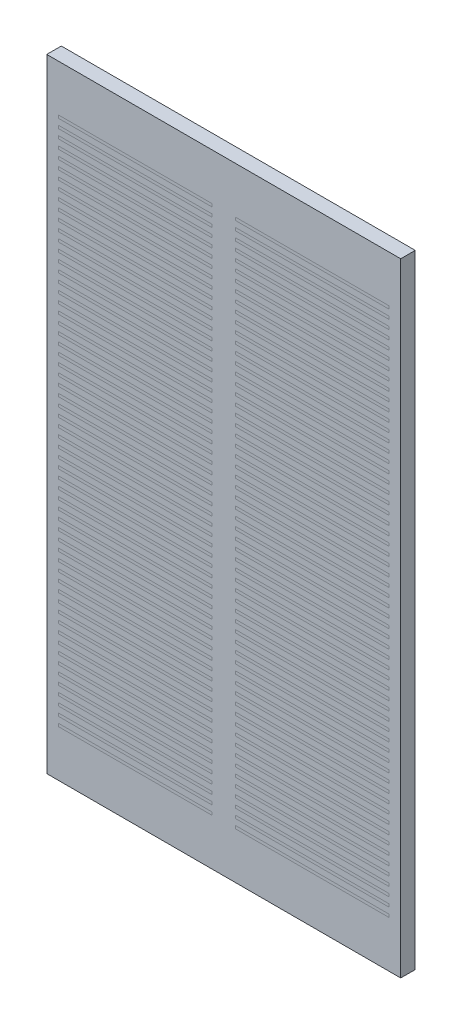
SolidWorks part; units mm, degrees
ref_plane "Alzado" through (0, 0, 0) normal (0, 0, 1) x (1, 0, 0)
ref_plane "Planta" through (0, 0, 0) normal (0, 1, 0) x (1, 0, 0)
ref_plane "Vista lateral" through (0, 0, 0) normal (1, 0, 0) x (0, 0, -1)
sketch "Croquis1" plane through (0, 0, 0) normal (0, 0, 1) x (1, 0, 0)
  line L1 (-30.4, 53.5) -> (30.4, 53.5)
  line L2 (-30.4, 53.5) -> (-30.4, -53.5)
  line L3 (-30.4, -53.5) -> (30.4, -53.5)
  line L4 (30.4, 53.5) -> (30.4, -53.5)
  line L5 (-30.4, 53.5) -> (30.4, -53.5) construction
  line L6 (-30.4, -53.5) -> (30.4, 53.5) construction
  point P0 (0, 0)
  dimension "D1" = 107
  dimension "D2" = 60.8
extrude "Saliente-Extruir1" add sketch "Croquis1" along normal blind 2.5
sketch "Croquis2" plane through (0, 0, 2.5) normal (0, 0, 1) x (1, 0, 0)
  line L0 (0, -53.5) -> (0, 53.5) construction
  line L124 (30.4, 53.5) -> (-30.4, 53.5) construction
  line L125 (30.4, -53.5) -> (30.4, 53.5) construction
  line L126 (2, 45.5) -> (28.4, 45.5)
  line L127 (2, 45.5) -> (2, 45)
  line L128 (2, 45) -> (28.4, 45)
  line L129 (28.4, 45.5) -> (28.4, 45)
  line L130 (2, 43.4661) -> (28.4, 43.4661)
  line L131 (2, 43.9661) -> (28.4, 43.9661)
  line L132 (2, 43.9661) -> (2, 43.4661)
  line L133 (28.4, 43.9661) -> (28.4, 43.4661)
  line L134 (2, 41.9322) -> (28.4, 41.9322)
  line L135 (2, 42.4322) -> (28.4, 42.4322)
  line L136 (2, 42.4322) -> (2, 41.9322)
  line L137 (28.4, 42.4322) -> (28.4, 41.9322)
  line L138 (2, 40.3983) -> (28.4, 40.3983)
  line L139 (2, 40.8983) -> (28.4, 40.8983)
  line L140 (2, 40.8983) -> (2, 40.3983)
  line L141 (28.4, 40.8983) -> (28.4, 40.3983)
  line L142 (2, 38.8644) -> (28.4, 38.8644)
  line L143 (2, 39.3644) -> (28.4, 39.3644)
  line L144 (2, 39.3644) -> (2, 38.8644)
  line L145 (28.4, 39.3644) -> (28.4, 38.8644)
  line L146 (2, 37.3305) -> (28.4, 37.3305)
  line L147 (2, 37.8305) -> (28.4, 37.8305)
  line L148 (2, 37.8305) -> (2, 37.3305)
  line L149 (28.4, 37.8305) -> (28.4, 37.3305)
  line L150 (2, 35.7966) -> (28.4, 35.7966)
  line L151 (2, 36.2966) -> (28.4, 36.2966)
  line L152 (2, 36.2966) -> (2, 35.7966)
  line L153 (28.4, 36.2966) -> (28.4, 35.7966)
  line L154 (2, 34.2627) -> (28.4, 34.2627)
  line L155 (2, 34.7627) -> (28.4, 34.7627)
  line L156 (2, 34.7627) -> (2, 34.2627)
  line L157 (28.4, 34.7627) -> (28.4, 34.2627)
  line L158 (2, 32.7288) -> (28.4, 32.7288)
  line L159 (2, 33.2288) -> (28.4, 33.2288)
  line L160 (2, 33.2288) -> (2, 32.7288)
  line L161 (28.4, 33.2288) -> (28.4, 32.7288)
  line L162 (2, 31.1949) -> (28.4, 31.1949)
  line L163 (2, 31.6949) -> (28.4, 31.6949)
  line L164 (2, 31.6949) -> (2, 31.1949)
  line L165 (28.4, 31.6949) -> (28.4, 31.1949)
  line L166 (2, 29.661) -> (28.4, 29.661)
  line L167 (2, 30.161) -> (28.4, 30.161)
  line L168 (2, 30.161) -> (2, 29.661)
  line L169 (28.4, 30.161) -> (28.4, 29.661)
  line L170 (2, 28.1271) -> (28.4, 28.1271)
  line L171 (2, 28.6271) -> (28.4, 28.6271)
  line L172 (2, 28.6271) -> (2, 28.1271)
  line L173 (28.4, 28.6271) -> (28.4, 28.1271)
  line L174 (2, 26.5932) -> (28.4, 26.5932)
  line L175 (2, 27.0932) -> (28.4, 27.0932)
  line L176 (2, 27.0932) -> (2, 26.5932)
  line L177 (28.4, 27.0932) -> (28.4, 26.5932)
  line L178 (2, 25.0593) -> (28.4, 25.0593)
  line L179 (2, 25.5593) -> (28.4, 25.5593)
  line L180 (2, 25.5593) -> (2, 25.0593)
  line L181 (28.4, 25.5593) -> (28.4, 25.0593)
  line L182 (2, 23.5254) -> (28.4, 23.5254)
  line L183 (2, 24.0254) -> (28.4, 24.0254)
  line L184 (2, 24.0254) -> (2, 23.5254)
  line L185 (28.4, 24.0254) -> (28.4, 23.5254)
  line L186 (2, 21.9915) -> (28.4, 21.9915)
  line L187 (2, 22.4915) -> (28.4, 22.4915)
  line L188 (2, 22.4915) -> (2, 21.9915)
  line L189 (28.4, 22.4915) -> (28.4, 21.9915)
  line L190 (2, 20.4576) -> (28.4, 20.4576)
  line L191 (2, 20.9576) -> (28.4, 20.9576)
  line L192 (2, 20.9576) -> (2, 20.4576)
  line L193 (28.4, 20.9576) -> (28.4, 20.4576)
  line L194 (2, 18.9237) -> (28.4, 18.9237)
  line L195 (2, 19.4237) -> (28.4, 19.4237)
  line L196 (2, 19.4237) -> (2, 18.9237)
  line L197 (28.4, 19.4237) -> (28.4, 18.9237)
  line L198 (2, 17.3898) -> (28.4, 17.3898)
  line L199 (2, 17.8898) -> (28.4, 17.8898)
  line L200 (2, 17.8898) -> (2, 17.3898)
  line L201 (28.4, 17.8898) -> (28.4, 17.3898)
  line L202 (2, 15.8559) -> (28.4, 15.8559)
  line L203 (2, 16.3559) -> (28.4, 16.3559)
  line L204 (2, 16.3559) -> (2, 15.8559)
  line L205 (28.4, 16.3559) -> (28.4, 15.8559)
  line L206 (2, 14.322) -> (28.4, 14.322)
  line L207 (2, 14.822) -> (28.4, 14.822)
  line L208 (2, 14.822) -> (2, 14.322)
  line L209 (28.4, 14.822) -> (28.4, 14.322)
  line L210 (2, 12.7881) -> (28.4, 12.7881)
  line L211 (2, 13.2881) -> (28.4, 13.2881)
  line L212 (2, 13.2881) -> (2, 12.7881)
  line L213 (28.4, 13.2881) -> (28.4, 12.7881)
  line L214 (2, 11.2542) -> (28.4, 11.2542)
  line L215 (2, 11.7542) -> (28.4, 11.7542)
  line L216 (2, 11.7542) -> (2, 11.2542)
  line L217 (28.4, 11.7542) -> (28.4, 11.2542)
  line L218 (2, 9.7203) -> (28.4, 9.7203)
  line L219 (2, 10.2203) -> (28.4, 10.2203)
  line L220 (2, 10.2203) -> (2, 9.7203)
  line L221 (28.4, 10.2203) -> (28.4, 9.7203)
  line L222 (2, 8.1864) -> (28.4, 8.1864)
  line L223 (2, 8.6864) -> (28.4, 8.6864)
  line L224 (2, 8.6864) -> (2, 8.1864)
  line L225 (28.4, 8.6864) -> (28.4, 8.1864)
  line L226 (2, 6.6525) -> (28.4, 6.6525)
  line L227 (2, 7.1525) -> (28.4, 7.1525)
  line L228 (2, 7.1525) -> (2, 6.6525)
  line L229 (28.4, 7.1525) -> (28.4, 6.6525)
  line L230 (2, 5.1186) -> (28.4, 5.1186)
  line L231 (2, 5.6186) -> (28.4, 5.6186)
  line L232 (2, 5.6186) -> (2, 5.1186)
  line L233 (28.4, 5.6186) -> (28.4, 5.1186)
  line L234 (2, 3.5847) -> (28.4, 3.5847)
  line L235 (2, 4.0847) -> (28.4, 4.0847)
  line L236 (2, 4.0847) -> (2, 3.5847)
  line L237 (28.4, 4.0847) -> (28.4, 3.5847)
  line L238 (2, 2.0508) -> (28.4, 2.0508)
  line L239 (2, 2.5508) -> (28.4, 2.5508)
  line L240 (2, 2.5508) -> (2, 2.0508)
  line L241 (28.4, 2.5508) -> (28.4, 2.0508)
  line L242 (2, 0.5169) -> (28.4, 0.5169)
  line L243 (2, 1.0169) -> (28.4, 1.0169)
  line L244 (2, 1.0169) -> (2, 0.5169)
  line L245 (28.4, 1.0169) -> (28.4, 0.5169)
  line L246 (2, -1.0169) -> (28.4, -1.0169)
  line L247 (2, -0.5169) -> (28.4, -0.5169)
  line L248 (2, -0.5169) -> (2, -1.0169)
  line L249 (28.4, -0.5169) -> (28.4, -1.0169)
  line L250 (2, -2.5508) -> (28.4, -2.5508)
  line L251 (2, -2.0508) -> (28.4, -2.0508)
  line L252 (2, -2.0508) -> (2, -2.5508)
  line L253 (28.4, -2.0508) -> (28.4, -2.5508)
  line L254 (2, -4.0847) -> (28.4, -4.0847)
  line L255 (2, -3.5847) -> (28.4, -3.5847)
  line L256 (2, -3.5847) -> (2, -4.0847)
  line L257 (28.4, -3.5847) -> (28.4, -4.0847)
  line L258 (2, -5.6186) -> (28.4, -5.6186)
  line L259 (2, -5.1186) -> (28.4, -5.1186)
  line L260 (2, -5.1186) -> (2, -5.6186)
  line L261 (28.4, -5.1186) -> (28.4, -5.6186)
  line L262 (2, -7.1525) -> (28.4, -7.1525)
  line L263 (2, -6.6525) -> (28.4, -6.6525)
  line L264 (2, -6.6525) -> (2, -7.1525)
  line L265 (28.4, -6.6525) -> (28.4, -7.1525)
  line L266 (2, -8.6864) -> (28.4, -8.6864)
  line L267 (2, -8.1864) -> (28.4, -8.1864)
  line L268 (2, -8.1864) -> (2, -8.6864)
  line L269 (28.4, -8.1864) -> (28.4, -8.6864)
  line L270 (2, -10.2203) -> (28.4, -10.2203)
  line L271 (2, -9.7203) -> (28.4, -9.7203)
  line L272 (2, -9.7203) -> (2, -10.2203)
  line L273 (28.4, -9.7203) -> (28.4, -10.2203)
  line L274 (2, -11.7542) -> (28.4, -11.7542)
  line L275 (2, -11.2542) -> (28.4, -11.2542)
  line L276 (2, -11.2542) -> (2, -11.7542)
  line L277 (28.4, -11.2542) -> (28.4, -11.7542)
  line L278 (2, -13.2881) -> (28.4, -13.2881)
  line L279 (2, -12.7881) -> (28.4, -12.7881)
  line L280 (2, -12.7881) -> (2, -13.2881)
  line L281 (28.4, -12.7881) -> (28.4, -13.2881)
  line L282 (2, -14.822) -> (28.4, -14.822)
  line L283 (2, -14.322) -> (28.4, -14.322)
  line L284 (2, -14.322) -> (2, -14.822)
  line L285 (28.4, -14.322) -> (28.4, -14.822)
  line L286 (2, -16.3559) -> (28.4, -16.3559)
  line L287 (2, -15.8559) -> (28.4, -15.8559)
  line L288 (2, -15.8559) -> (2, -16.3559)
  line L289 (28.4, -15.8559) -> (28.4, -16.3559)
  line L290 (2, -17.8898) -> (28.4, -17.8898)
  line L291 (2, -17.3898) -> (28.4, -17.3898)
  line L292 (2, -17.3898) -> (2, -17.8898)
  line L293 (28.4, -17.3898) -> (28.4, -17.8898)
  line L294 (2, -19.4237) -> (28.4, -19.4237)
  line L295 (2, -18.9237) -> (28.4, -18.9237)
  line L296 (2, -18.9237) -> (2, -19.4237)
  line L297 (28.4, -18.9237) -> (28.4, -19.4237)
  line L298 (2, -20.9576) -> (28.4, -20.9576)
  line L299 (2, -20.4576) -> (28.4, -20.4576)
  line L300 (2, -20.4576) -> (2, -20.9576)
  line L301 (28.4, -20.4576) -> (28.4, -20.9576)
  line L302 (2, -22.4915) -> (28.4, -22.4915)
  line L303 (2, -21.9915) -> (28.4, -21.9915)
  line L304 (2, -21.9915) -> (2, -22.4915)
  line L305 (28.4, -21.9915) -> (28.4, -22.4915)
  line L306 (2, -24.0254) -> (28.4, -24.0254)
  line L307 (2, -23.5254) -> (28.4, -23.5254)
  line L308 (2, -23.5254) -> (2, -24.0254)
  line L309 (28.4, -23.5254) -> (28.4, -24.0254)
  line L310 (2, -25.5593) -> (28.4, -25.5593)
  line L311 (2, -25.0593) -> (28.4, -25.0593)
  line L312 (2, -25.0593) -> (2, -25.5593)
  line L313 (28.4, -25.0593) -> (28.4, -25.5593)
  line L314 (2, -27.0932) -> (28.4, -27.0932)
  line L315 (2, -26.5932) -> (28.4, -26.5932)
  line L316 (2, -26.5932) -> (2, -27.0932)
  line L317 (28.4, -26.5932) -> (28.4, -27.0932)
  line L318 (2, -28.6271) -> (28.4, -28.6271)
  line L319 (2, -28.1271) -> (28.4, -28.1271)
  line L320 (2, -28.1271) -> (2, -28.6271)
  line L321 (28.4, -28.1271) -> (28.4, -28.6271)
  line L322 (2, -30.161) -> (28.4, -30.161)
  line L323 (2, -29.661) -> (28.4, -29.661)
  line L324 (2, -29.661) -> (2, -30.161)
  line L325 (28.4, -29.661) -> (28.4, -30.161)
  line L326 (2, -31.6949) -> (28.4, -31.6949)
  line L327 (2, -31.1949) -> (28.4, -31.1949)
  line L328 (2, -31.1949) -> (2, -31.6949)
  line L329 (28.4, -31.1949) -> (28.4, -31.6949)
  line L330 (2, -33.2288) -> (28.4, -33.2288)
  line L331 (2, -32.7288) -> (28.4, -32.7288)
  line L332 (2, -32.7288) -> (2, -33.2288)
  line L333 (28.4, -32.7288) -> (28.4, -33.2288)
  line L334 (2, -34.7627) -> (28.4, -34.7627)
  line L335 (2, -34.2627) -> (28.4, -34.2627)
  line L336 (2, -34.2627) -> (2, -34.7627)
  line L337 (28.4, -34.2627) -> (28.4, -34.7627)
  line L338 (2, -36.2966) -> (28.4, -36.2966)
  line L339 (2, -35.7966) -> (28.4, -35.7966)
  line L340 (2, -35.7966) -> (2, -36.2966)
  line L341 (28.4, -35.7966) -> (28.4, -36.2966)
  line L342 (2, -37.8305) -> (28.4, -37.8305)
  line L343 (2, -37.3305) -> (28.4, -37.3305)
  line L344 (2, -37.3305) -> (2, -37.8305)
  line L345 (28.4, -37.3305) -> (28.4, -37.8305)
  line L346 (2, -39.3644) -> (28.4, -39.3644)
  line L347 (2, -38.8644) -> (28.4, -38.8644)
  line L348 (2, -38.8644) -> (2, -39.3644)
  line L349 (28.4, -38.8644) -> (28.4, -39.3644)
  line L350 (2, -40.8983) -> (28.4, -40.8983)
  line L351 (2, -40.3983) -> (28.4, -40.3983)
  line L352 (2, -40.3983) -> (2, -40.8983)
  line L353 (28.4, -40.3983) -> (28.4, -40.8983)
  line L354 (2, -42.4322) -> (28.4, -42.4322)
  line L355 (2, -41.9322) -> (28.4, -41.9322)
  line L356 (2, -41.9322) -> (2, -42.4322)
  line L357 (28.4, -41.9322) -> (28.4, -42.4322)
  line L358 (2, -43.9661) -> (28.4, -43.9661)
  line L359 (2, -43.4661) -> (28.4, -43.4661)
  line L360 (2, -43.4661) -> (2, -43.9661)
  line L361 (28.4, -43.4661) -> (28.4, -43.9661)
  line L362 (2, -45.5) -> (28.4, -45.5)
  line L363 (2, -45) -> (28.4, -45)
  line L364 (2, -45) -> (2, -45.5)
  line L365 (28.4, -45) -> (28.4, -45.5)
  line L366 (-30.4, -53.5) -> (30.4, -53.5) construction
  line L367 (-28.4, -45) -> (-28.4, -45.5)
  line L368 (-2, -45) -> (-2, -45.5)
  line L369 (-2, -45) -> (-28.4, -45)
  line L370 (-2, -45.5) -> (-28.4, -45.5)
  line L371 (-28.4, -43.4661) -> (-28.4, -43.9661)
  line L372 (-2, -43.4661) -> (-2, -43.9661)
  line L373 (-2, -43.4661) -> (-28.4, -43.4661)
  line L374 (-2, -43.9661) -> (-28.4, -43.9661)
  line L375 (-28.4, -41.9322) -> (-28.4, -42.4322)
  line L376 (-2, -41.9322) -> (-2, -42.4322)
  line L377 (-2, -41.9322) -> (-28.4, -41.9322)
  line L378 (-2, -42.4322) -> (-28.4, -42.4322)
  line L379 (-28.4, -40.3983) -> (-28.4, -40.8983)
  line L380 (-2, -40.3983) -> (-2, -40.8983)
  line L381 (-2, -40.3983) -> (-28.4, -40.3983)
  line L382 (-2, -40.8983) -> (-28.4, -40.8983)
  line L383 (-28.4, -38.8644) -> (-28.4, -39.3644)
  line L384 (-2, -38.8644) -> (-2, -39.3644)
  line L385 (-2, -38.8644) -> (-28.4, -38.8644)
  line L386 (-2, -39.3644) -> (-28.4, -39.3644)
  line L387 (-28.4, -37.3305) -> (-28.4, -37.8305)
  line L388 (-2, -37.3305) -> (-2, -37.8305)
  line L389 (-2, -37.3305) -> (-28.4, -37.3305)
  line L390 (-2, -37.8305) -> (-28.4, -37.8305)
  line L391 (-28.4, -35.7966) -> (-28.4, -36.2966)
  line L392 (-2, -35.7966) -> (-2, -36.2966)
  line L393 (-2, -35.7966) -> (-28.4, -35.7966)
  line L394 (-2, -36.2966) -> (-28.4, -36.2966)
  line L395 (-28.4, -34.2627) -> (-28.4, -34.7627)
  line L396 (-2, -34.2627) -> (-2, -34.7627)
  line L397 (-2, -34.2627) -> (-28.4, -34.2627)
  line L398 (-2, -34.7627) -> (-28.4, -34.7627)
  line L399 (-28.4, -32.7288) -> (-28.4, -33.2288)
  line L400 (-2, -32.7288) -> (-2, -33.2288)
  line L401 (-2, -32.7288) -> (-28.4, -32.7288)
  line L402 (-2, -33.2288) -> (-28.4, -33.2288)
  line L403 (-28.4, -31.1949) -> (-28.4, -31.6949)
  line L404 (-2, -31.1949) -> (-2, -31.6949)
  line L405 (-2, -31.1949) -> (-28.4, -31.1949)
  line L406 (-2, -31.6949) -> (-28.4, -31.6949)
  line L407 (-28.4, -29.661) -> (-28.4, -30.161)
  line L408 (-2, -29.661) -> (-2, -30.161)
  line L409 (-2, -29.661) -> (-28.4, -29.661)
  line L410 (-2, -30.161) -> (-28.4, -30.161)
  line L411 (-28.4, -28.1271) -> (-28.4, -28.6271)
  line L412 (-2, -28.1271) -> (-2, -28.6271)
  line L413 (-2, -28.1271) -> (-28.4, -28.1271)
  line L414 (-2, -28.6271) -> (-28.4, -28.6271)
  line L415 (-28.4, -26.5932) -> (-28.4, -27.0932)
  line L416 (-2, -26.5932) -> (-2, -27.0932)
  line L417 (-2, -26.5932) -> (-28.4, -26.5932)
  line L418 (-2, -27.0932) -> (-28.4, -27.0932)
  line L419 (-28.4, -25.0593) -> (-28.4, -25.5593)
  line L420 (-2, -25.0593) -> (-2, -25.5593)
  line L421 (-2, -25.0593) -> (-28.4, -25.0593)
  line L422 (-2, -25.5593) -> (-28.4, -25.5593)
  line L423 (-28.4, -23.5254) -> (-28.4, -24.0254)
  line L424 (-2, -23.5254) -> (-2, -24.0254)
  line L425 (-2, -23.5254) -> (-28.4, -23.5254)
  line L426 (-2, -24.0254) -> (-28.4, -24.0254)
  line L427 (-28.4, -21.9915) -> (-28.4, -22.4915)
  line L428 (-2, -21.9915) -> (-2, -22.4915)
  line L429 (-2, -21.9915) -> (-28.4, -21.9915)
  line L430 (-2, -22.4915) -> (-28.4, -22.4915)
  line L431 (-28.4, -20.4576) -> (-28.4, -20.9576)
  line L432 (-2, -20.4576) -> (-2, -20.9576)
  line L433 (-2, -20.4576) -> (-28.4, -20.4576)
  line L434 (-2, -20.9576) -> (-28.4, -20.9576)
  line L435 (-28.4, -18.9237) -> (-28.4, -19.4237)
  line L436 (-2, -18.9237) -> (-2, -19.4237)
  line L437 (-2, -18.9237) -> (-28.4, -18.9237)
  line L438 (-2, -19.4237) -> (-28.4, -19.4237)
  line L439 (-28.4, -17.3898) -> (-28.4, -17.8898)
  line L440 (-2, -17.3898) -> (-2, -17.8898)
  line L441 (-2, -17.3898) -> (-28.4, -17.3898)
  line L442 (-2, -17.8898) -> (-28.4, -17.8898)
  line L443 (-28.4, -15.8559) -> (-28.4, -16.3559)
  line L444 (-2, -15.8559) -> (-2, -16.3559)
  line L445 (-2, -15.8559) -> (-28.4, -15.8559)
  line L446 (-2, -16.3559) -> (-28.4, -16.3559)
  line L447 (-28.4, -14.322) -> (-28.4, -14.822)
  line L448 (-2, -14.322) -> (-2, -14.822)
  line L449 (-2, -14.322) -> (-28.4, -14.322)
  line L450 (-2, -14.822) -> (-28.4, -14.822)
  line L451 (-28.4, -12.7881) -> (-28.4, -13.2881)
  line L452 (-2, -12.7881) -> (-2, -13.2881)
  line L453 (-2, -12.7881) -> (-28.4, -12.7881)
  line L454 (-2, -13.2881) -> (-28.4, -13.2881)
  line L455 (-28.4, -11.2542) -> (-28.4, -11.7542)
  line L456 (-2, -11.2542) -> (-2, -11.7542)
  line L457 (-2, -11.2542) -> (-28.4, -11.2542)
  line L458 (-2, -11.7542) -> (-28.4, -11.7542)
  line L459 (-28.4, -9.7203) -> (-28.4, -10.2203)
  line L460 (-2, -9.7203) -> (-2, -10.2203)
  line L461 (-2, -9.7203) -> (-28.4, -9.7203)
  line L462 (-2, -10.2203) -> (-28.4, -10.2203)
  line L463 (-28.4, -8.1864) -> (-28.4, -8.6864)
  line L464 (-2, -8.1864) -> (-2, -8.6864)
  line L465 (-2, -8.1864) -> (-28.4, -8.1864)
  line L466 (-2, -8.6864) -> (-28.4, -8.6864)
  line L467 (-28.4, -6.6525) -> (-28.4, -7.1525)
  line L468 (-2, -6.6525) -> (-2, -7.1525)
  line L469 (-2, -6.6525) -> (-28.4, -6.6525)
  line L470 (-2, -7.1525) -> (-28.4, -7.1525)
  line L471 (-28.4, -5.1186) -> (-28.4, -5.6186)
  line L472 (-2, -5.1186) -> (-2, -5.6186)
  line L473 (-2, -5.1186) -> (-28.4, -5.1186)
  line L474 (-2, -5.6186) -> (-28.4, -5.6186)
  line L475 (-28.4, -3.5847) -> (-28.4, -4.0847)
  line L476 (-2, -3.5847) -> (-2, -4.0847)
  line L477 (-2, -3.5847) -> (-28.4, -3.5847)
  line L478 (-2, -4.0847) -> (-28.4, -4.0847)
  line L479 (-28.4, -2.0508) -> (-28.4, -2.5508)
  line L480 (-2, -2.0508) -> (-2, -2.5508)
  line L481 (-2, -2.0508) -> (-28.4, -2.0508)
  line L482 (-2, -2.5508) -> (-28.4, -2.5508)
  line L483 (-28.4, -0.5169) -> (-28.4, -1.0169)
  line L484 (-2, -0.5169) -> (-2, -1.0169)
  line L485 (-2, -0.5169) -> (-28.4, -0.5169)
  line L486 (-2, -1.0169) -> (-28.4, -1.0169)
  line L487 (-28.4, 1.0169) -> (-28.4, 0.5169)
  line L488 (-2, 1.0169) -> (-2, 0.5169)
  line L489 (-2, 1.0169) -> (-28.4, 1.0169)
  line L490 (-2, 0.5169) -> (-28.4, 0.5169)
  line L491 (-28.4, 2.5508) -> (-28.4, 2.0508)
  line L492 (-2, 2.5508) -> (-2, 2.0508)
  line L493 (-2, 2.5508) -> (-28.4, 2.5508)
  line L494 (-2, 2.0508) -> (-28.4, 2.0508)
  line L495 (-28.4, 4.0847) -> (-28.4, 3.5847)
  line L496 (-2, 4.0847) -> (-2, 3.5847)
  line L497 (-2, 4.0847) -> (-28.4, 4.0847)
  line L498 (-2, 3.5847) -> (-28.4, 3.5847)
  line L499 (-28.4, 5.6186) -> (-28.4, 5.1186)
  line L500 (-2, 5.6186) -> (-2, 5.1186)
  line L501 (-2, 5.6186) -> (-28.4, 5.6186)
  line L502 (-2, 5.1186) -> (-28.4, 5.1186)
  line L503 (-28.4, 7.1525) -> (-28.4, 6.6525)
  line L504 (-2, 7.1525) -> (-2, 6.6525)
  line L505 (-2, 7.1525) -> (-28.4, 7.1525)
  line L506 (-2, 6.6525) -> (-28.4, 6.6525)
  line L507 (-28.4, 8.6864) -> (-28.4, 8.1864)
  line L508 (-2, 8.6864) -> (-2, 8.1864)
  line L509 (-2, 8.6864) -> (-28.4, 8.6864)
  line L510 (-2, 8.1864) -> (-28.4, 8.1864)
  line L511 (-28.4, 10.2203) -> (-28.4, 9.7203)
  line L512 (-2, 10.2203) -> (-2, 9.7203)
  line L513 (-2, 10.2203) -> (-28.4, 10.2203)
  line L514 (-2, 9.7203) -> (-28.4, 9.7203)
  line L515 (-28.4, 11.7542) -> (-28.4, 11.2542)
  line L516 (-2, 11.7542) -> (-2, 11.2542)
  line L517 (-2, 11.7542) -> (-28.4, 11.7542)
  line L518 (-2, 11.2542) -> (-28.4, 11.2542)
  line L519 (-28.4, 13.2881) -> (-28.4, 12.7881)
  line L520 (-2, 13.2881) -> (-2, 12.7881)
  line L521 (-2, 13.2881) -> (-28.4, 13.2881)
  line L522 (-2, 12.7881) -> (-28.4, 12.7881)
  line L523 (-28.4, 14.822) -> (-28.4, 14.322)
  line L524 (-2, 14.822) -> (-2, 14.322)
  line L525 (-2, 14.822) -> (-28.4, 14.822)
  line L526 (-2, 14.322) -> (-28.4, 14.322)
  line L527 (-28.4, 16.3559) -> (-28.4, 15.8559)
  line L528 (-2, 16.3559) -> (-2, 15.8559)
  line L529 (-2, 16.3559) -> (-28.4, 16.3559)
  line L530 (-2, 15.8559) -> (-28.4, 15.8559)
  line L531 (-28.4, 17.8898) -> (-28.4, 17.3898)
  line L532 (-2, 17.8898) -> (-2, 17.3898)
  line L533 (-2, 17.8898) -> (-28.4, 17.8898)
  line L534 (-2, 17.3898) -> (-28.4, 17.3898)
  line L535 (-28.4, 19.4237) -> (-28.4, 18.9237)
  line L536 (-2, 19.4237) -> (-2, 18.9237)
  line L537 (-2, 19.4237) -> (-28.4, 19.4237)
  line L538 (-2, 18.9237) -> (-28.4, 18.9237)
  line L539 (-28.4, 20.9576) -> (-28.4, 20.4576)
  line L540 (-2, 20.9576) -> (-2, 20.4576)
  line L541 (-2, 20.9576) -> (-28.4, 20.9576)
  line L542 (-2, 20.4576) -> (-28.4, 20.4576)
  line L543 (-28.4, 22.4915) -> (-28.4, 21.9915)
  line L544 (-2, 22.4915) -> (-2, 21.9915)
  line L545 (-2, 22.4915) -> (-28.4, 22.4915)
  line L546 (-2, 21.9915) -> (-28.4, 21.9915)
  line L547 (-28.4, 24.0254) -> (-28.4, 23.5254)
  line L548 (-2, 24.0254) -> (-2, 23.5254)
  line L549 (-2, 24.0254) -> (-28.4, 24.0254)
  line L550 (-2, 23.5254) -> (-28.4, 23.5254)
  line L551 (-28.4, 25.5593) -> (-28.4, 25.0593)
  line L552 (-2, 25.5593) -> (-2, 25.0593)
  line L553 (-2, 25.5593) -> (-28.4, 25.5593)
  line L554 (-2, 25.0593) -> (-28.4, 25.0593)
  line L555 (-28.4, 27.0932) -> (-28.4, 26.5932)
  line L556 (-2, 27.0932) -> (-2, 26.5932)
  line L557 (-2, 27.0932) -> (-28.4, 27.0932)
  line L558 (-2, 26.5932) -> (-28.4, 26.5932)
  line L559 (-28.4, 28.6271) -> (-28.4, 28.1271)
  line L560 (-2, 28.6271) -> (-2, 28.1271)
  line L561 (-2, 28.6271) -> (-28.4, 28.6271)
  line L562 (-2, 28.1271) -> (-28.4, 28.1271)
  line L563 (-28.4, 30.161) -> (-28.4, 29.661)
  line L564 (-2, 30.161) -> (-2, 29.661)
  line L565 (-2, 30.161) -> (-28.4, 30.161)
  line L566 (-2, 29.661) -> (-28.4, 29.661)
  line L567 (-28.4, 31.6949) -> (-28.4, 31.1949)
  line L568 (-2, 31.6949) -> (-2, 31.1949)
  line L569 (-2, 31.6949) -> (-28.4, 31.6949)
  line L570 (-2, 31.1949) -> (-28.4, 31.1949)
  line L571 (-28.4, 33.2288) -> (-28.4, 32.7288)
  line L572 (-2, 33.2288) -> (-2, 32.7288)
  line L573 (-2, 33.2288) -> (-28.4, 33.2288)
  line L574 (-2, 32.7288) -> (-28.4, 32.7288)
  line L575 (-28.4, 34.7627) -> (-28.4, 34.2627)
  line L576 (-2, 34.7627) -> (-2, 34.2627)
  line L577 (-2, 34.7627) -> (-28.4, 34.7627)
  line L578 (-2, 34.2627) -> (-28.4, 34.2627)
  line L579 (-28.4, 36.2966) -> (-28.4, 35.7966)
  line L580 (-2, 36.2966) -> (-2, 35.7966)
  line L581 (-2, 36.2966) -> (-28.4, 36.2966)
  line L582 (-2, 35.7966) -> (-28.4, 35.7966)
  line L583 (-28.4, 37.8305) -> (-28.4, 37.3305)
  line L584 (-2, 37.8305) -> (-2, 37.3305)
  line L585 (-2, 37.8305) -> (-28.4, 37.8305)
  line L586 (-2, 37.3305) -> (-28.4, 37.3305)
  line L587 (-28.4, 39.3644) -> (-28.4, 38.8644)
  line L588 (-2, 39.3644) -> (-2, 38.8644)
  line L589 (-2, 39.3644) -> (-28.4, 39.3644)
  line L590 (-2, 38.8644) -> (-28.4, 38.8644)
  line L591 (-28.4, 40.8983) -> (-28.4, 40.3983)
  line L592 (-2, 40.8983) -> (-2, 40.3983)
  line L593 (-2, 40.8983) -> (-28.4, 40.8983)
  line L594 (-2, 40.3983) -> (-28.4, 40.3983)
  line L595 (-28.4, 42.4322) -> (-28.4, 41.9322)
  line L596 (-2, 42.4322) -> (-2, 41.9322)
  line L597 (-2, 42.4322) -> (-28.4, 42.4322)
  line L598 (-2, 41.9322) -> (-28.4, 41.9322)
  line L599 (-28.4, 43.9661) -> (-28.4, 43.4661)
  line L600 (-2, 43.9661) -> (-2, 43.4661)
  line L601 (-2, 43.9661) -> (-28.4, 43.9661)
  line L602 (-2, 43.4661) -> (-28.4, 43.4661)
  line L603 (-28.4, 45.5) -> (-28.4, 45)
  line L604 (-2, 45) -> (-28.4, 45)
  line L605 (-2, 45.5) -> (-2, 45)
  line L606 (-2, 45.5) -> (-28.4, 45.5)
  point P5 (0, 0)
  point P12 (30.4, 0)
  dimension "D1" = 2
  dimension "D2" = 8
  dimension "D3" = 4
  dimension "D5" = 60
  dimension "D4" = 0.5
  dimension "D6" = 8
split line "Línea de partición5"
sketch "Croquis4" plane through (0, 0, 0) normal (0, 0, -1) x (-1, 0, 0)
  line L0 (-30.4, 0) -> (30.4, 0) construction
  line L1 (-30.4, 53.5) -> (30.4, 53.5) construction
  line L2 (30.4, 53.5) -> (30.4, -53.5) construction
  line L3 (9.4, 39) -> (-30.4, 39) construction
  line L4 (-30.4, -53.5) -> (-30.4, 53.5) construction
  circle A0 centre (9.4, 39) radius 1.8
  circle A1 centre (-19.6, 39) radius 1.8
  circle A2 centre (-19.6, -39) radius 1.8
  circle A3 centre (9.4, -39) radius 1.8
  point P8 (0, 0)
  point P17 (0, 0)
  dimension "D1" = 3.6
  dimension "D2" = 14.5
  dimension "D3" = 21
  dimension "D4" = 29
split line "Línea de partición6"
